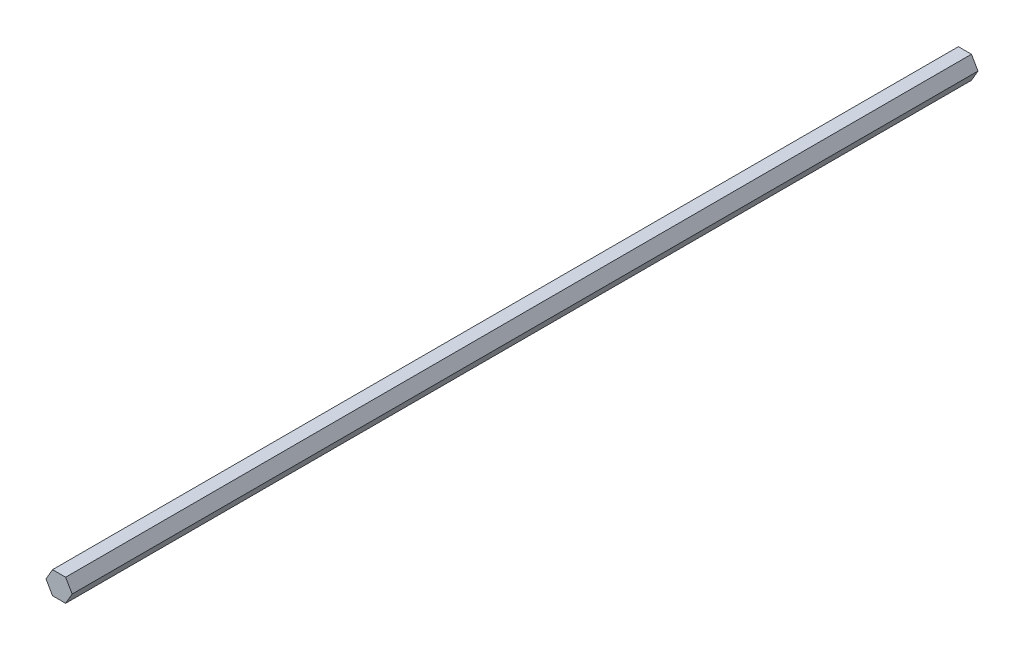
SolidWorks part; units mm, degrees
ref_plane "Front Plane" through (0, 0, 0) normal (0, 0, 1) x (1, 0, 0)
ref_plane "Top Plane" through (0, 0, 0) normal (0, 1, 0) x (1, 0, 0)
ref_plane "Right Plane" through (0, 0, 0) normal (1, 0, 0) x (0, 0, -1)
sketch "Sketch1" plane through (0, 0, 0) normal (0, 0, 1) x (1, 0, 0)
  line L1 (2.8868, 0) -> (1.4434, 2.5)
  line L2 (1.4434, 2.5) -> (-1.4434, 2.5)
  line L3 (-1.4434, 2.5) -> (-2.8868, 0)
  line L4 (-2.8868, 0) -> (-1.4434, -2.5)
  line L5 (-1.4434, -2.5) -> (1.4434, -2.5)
  line L6 (1.4434, -2.5) -> (2.8868, 0)
  circle A0 centre (0, 0) radius 2.5 construction
extrude "Boss-Extrude1" add sketch "Sketch1" along normal blind 200
